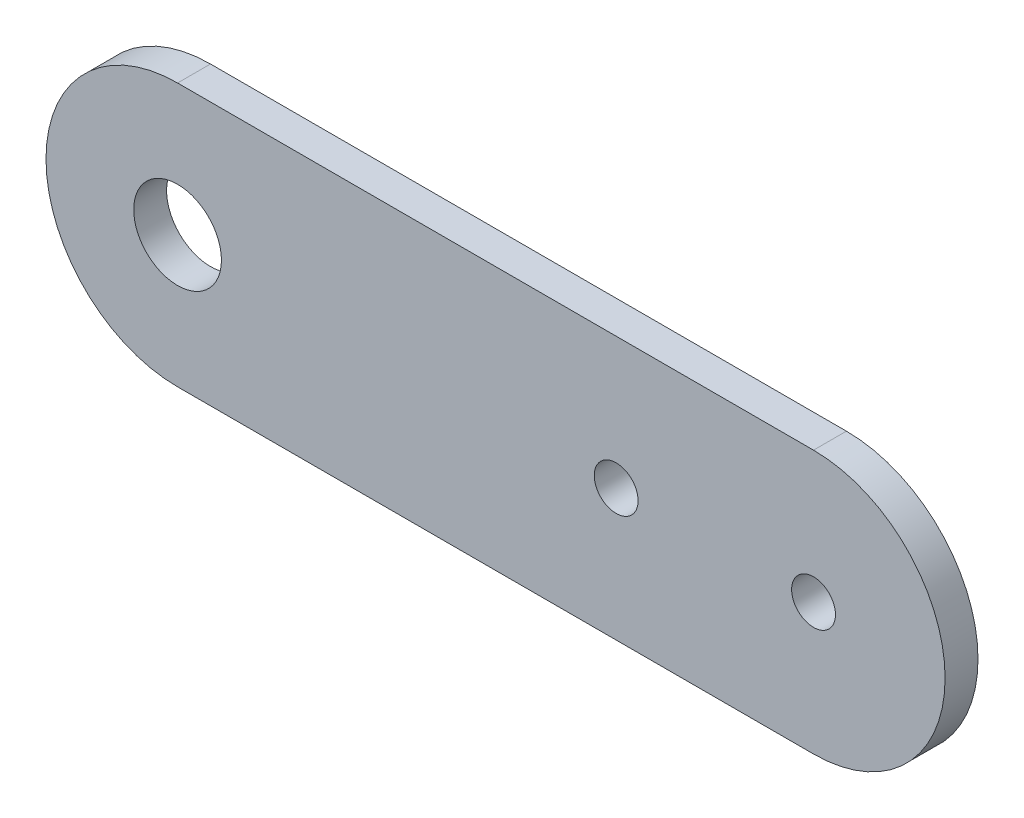
SolidWorks part; units mm, degrees
ref_plane "Front Plane" through (0, 0, 0) normal (0, 0, 1) x (1, 0, 0)
ref_plane "Top Plane" through (0, 0, 0) normal (0, 1, 0) x (1, 0, 0)
ref_plane "Right Plane" through (0, 0, 0) normal (1, 0, 0) x (0, 0, -1)
sketch "Sketch2" plane through (0, 0, 0) normal (0, 0, 1) x (1, 0, 0)
  line L0 (0, 0) -> (-9, 0) construction
  line L1 (0, 6) -> (0, -6) construction
  line L2 (0, 6) -> (-29, 6)
  line L3 (0, -6) -> (-29, -6)
  circle A0 centre (0, 0) radius 1
  arc A1 (0, -6) -> (0, 6) centre (0, 0) ccw
  circle A2 centre (-9, 0) radius 1
  arc A3 (-29, 6) -> (-29, -6) centre (-29, 0) ccw
  circle A4 centre (-29, 0) radius 2
extrude "Boss-Extrude1" add sketch "Sketch2" along normal blind 1.5
